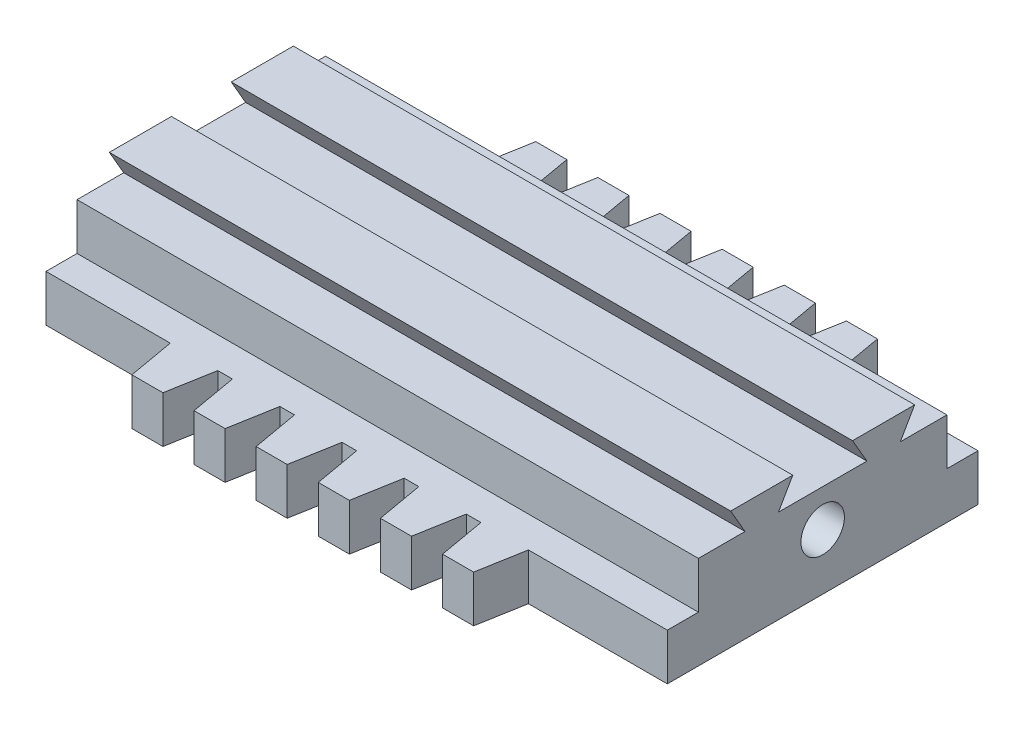
SolidWorks part; units mm, degrees
material "Cast Alloy Steel"
ref_plane "Front Plane" through (0, 0, 0) normal (0, 0, 1) x (1, 0, 0)
ref_plane "Top Plane" through (0, 0, 0) normal (0, 1, 0) x (1, 0, 0)
ref_plane "Right Plane" through (0, 0, 0) normal (1, 0, 0) x (0, 0, -1)
sketch "Sketch1" plane through (0, 0, 0) normal (0, 1, 0) x (1, 0, 0)
  line L0 (-60, 50) -> (-57.3551, 65)
  line L1 (-100, 50) -> (-60, 50)
  line L2 (-100, 50) -> (-100, -50)
  line L4 (100, 50) -> (100, -50)
  line L5 (-57.3551, 65) -> (-47.3551, 65)
  line L6 (-47.3551, 65) -> (-44.7102, 50)
  line L7 (-40, 50) -> (-37.3551, 65)
  line L8 (-37.3551, 65) -> (-27.3551, 65)
  line L9 (-27.3551, 65) -> (-24.7102, 50)
  line L10 (-20, 50) -> (-17.3551, 65)
  line L11 (-17.3551, 65) -> (-7.3551, 65)
  line L12 (-7.3551, 65) -> (-4.7102, 50)
  line L13 (0, 50) -> (2.6449, 65)
  line L14 (2.6449, 65) -> (12.6449, 65)
  line L15 (12.6449, 65) -> (15.2898, 50)
  line L16 (20, 50) -> (22.6449, 65)
  line L17 (22.6449, 65) -> (32.6449, 65)
  line L18 (32.6449, 65) -> (35.2898, 50)
  line L19 (40, 50) -> (42.6449, 65)
  line L20 (42.6449, 65) -> (52.6449, 65)
  line L21 (52.6449, 65) -> (55.2898, 50)
  line L22 (-110.8441, 0) -> (158.6713, 0) construction
  line L23 (-44.7102, 50) -> (-40, 50)
  line L24 (-24.7102, 50) -> (-20, 50)
  line L25 (-4.7102, 50) -> (0, 50)
  line L26 (15.2898, 50) -> (20, 50)
  line L27 (35.2898, 50) -> (40, 50)
  line L28 (55.2898, 50) -> (100, 50)
  line L29 (55.2898, -50) -> (100, -50)
  line L30 (35.2898, -50) -> (40, -50)
  line L31 (15.2898, -50) -> (20, -50)
  line L32 (-4.7102, -50) -> (0, -50)
  line L33 (-24.7102, -50) -> (-20, -50)
  line L34 (-44.7102, -50) -> (-40, -50)
  line L35 (52.6449, -65) -> (55.2898, -50)
  line L36 (42.6449, -65) -> (52.6449, -65)
  line L37 (40, -50) -> (42.6449, -65)
  line L38 (32.6449, -65) -> (35.2898, -50)
  line L39 (22.6449, -65) -> (32.6449, -65)
  line L40 (20, -50) -> (22.6449, -65)
  line L41 (12.6449, -65) -> (15.2898, -50)
  line L42 (2.6449, -65) -> (12.6449, -65)
  line L43 (0, -50) -> (2.6449, -65)
  line L44 (-7.3551, -65) -> (-4.7102, -50)
  line L45 (-17.3551, -65) -> (-7.3551, -65)
  line L46 (-20, -50) -> (-17.3551, -65)
  line L47 (-27.3551, -65) -> (-24.7102, -50)
  line L48 (-37.3551, -65) -> (-27.3551, -65)
  line L49 (-40, -50) -> (-37.3551, -65)
  line L50 (-47.3551, -65) -> (-44.7102, -50)
  line L51 (-57.3551, -65) -> (-47.3551, -65)
  line L52 (-100, -50) -> (-60, -50)
  line L53 (-60, -50) -> (-57.3551, -65)
  point P32 (100, 0)
  point P33 (-100, 0)
  dimension "D4" = 100
  dimension "D5" = 100
  dimension "D6" = 100
  dimension "D7" = 10
  dimension "D8" = 40
  dimension "D9" = 15
  dimension "D10" = 6
extrude "Boss-Extrude1" add sketch "Sketch1" along normal blind 15 contours L29 L4 L28 L21 L20 L19 L27 L18 L17 L16 L26 L15 L14 L13 L25 L12 L11 L10 L24 L9 L8 L7 L23 L6 L5 L0 L1 L2 L52 L53 L51 L50 L34 L49 L48 L47 L33 L46 L45 L44 L32 L43 L42 L41 L31 L40 L39 L38 L30 L37 L36 L35
sketch "Sketch2" plane through (0, 15, 0) normal (0, 1, 0) x (1, 0, 0)
  line L0 (-100, 50) -> (-100, -50) construction
  line L1 (-100, -40) -> (100, -40)
  line L2 (-100, -40) -> (-100, 40)
  line L3 (-100, 40) -> (100, 40)
  line L4 (100, -40) -> (100, 40)
  line L5 (100, 50) -> (100, -50) construction
  line L6 (55.2898, 50) -> (100, 50) construction
  line L7 (55.2898, -50) -> (100, -50) construction
  dimension "D1" = 10
  dimension "D2" = 10
extrude "Boss-Extrude2" add sketch "Sketch2" along normal blind 15 contours L1 L4 L3 L2
sketch "Sketch3" plane through (-100, 0, 0) normal (-1, 0, 0) x (0, 0, 1)
  line L0 (0, 0) -> (0, 52.7438) construction
  line L1 (25, 30) -> (29.6188, 38)
  line L2 (40, 30) -> (-40, 30) construction
  line L3 (29.6188, 38) -> (9.6188, 38)
  line L4 (9.6188, 38) -> (14.2376, 30)
  line L5 (25, 30) -> (14.2376, 30)
  line L6 (-25, 30) -> (-14.2376, 30)
  line L7 (-9.6188, 38) -> (-14.2376, 30)
  line L8 (-29.6188, 38) -> (-9.6188, 38)
  line L9 (-25, 30) -> (-29.6188, 38)
  dimension "D1" = 60
  dimension "D2" = 60
  dimension "D3" = 20
  dimension "D4" = 15
  dimension "D5" = 8
extrude "Boss-Extrude3" add sketch "Sketch3" against normal up to vertex (200 mm away)
sketch "Sketch4" plane through (-100, 0, 0) normal (-1, 0, 0) x (0, 0, 1)
  line L0 (14.2376, 30) -> (-14.2376, 30) construction
  circle A0 centre (0, 18) radius 7
  dimension "D2" = 14
  dimension "D1" = 12
extrude "Cut-Extrude1" cut sketch "Sketch4" against normal through all both and the other way through all contours A0
